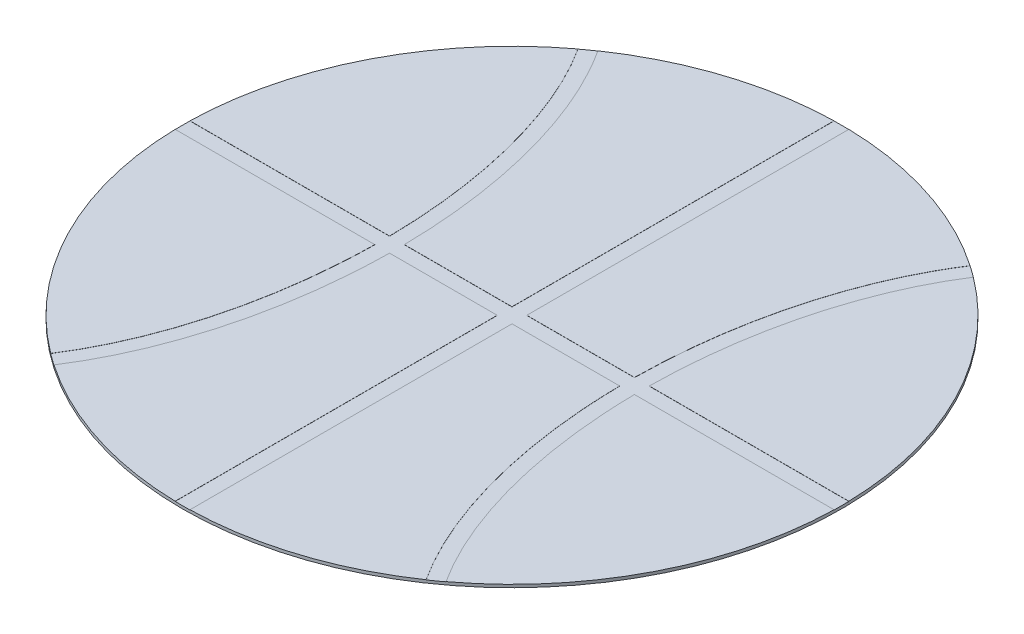
SolidWorks part; units mm, degrees
ref_plane "Front Plane" through (0, 0, 0) normal (0, 0, 1) x (1, 0, 0)
ref_plane "Top Plane" through (0, 0, 0) normal (0, 1, 0) x (1, 0, 0)
ref_plane "Right Plane" through (0, 0, 0) normal (1, 0, 0) x (0, 0, -1)
sketch "Sketch1" plane through (0, 0, 0) normal (0, 1, 0) x (1, 0, 0)
  circle A0 centre (0, 0) radius 22.3
  dimension "D1" = 44.6
extrude "Boss-Extrude1" add sketch "Sketch1" along normal blind 0.2
sketch "Sketch2" plane through (0, 0.2, 0) normal (0, 1, 0) x (1, 0, 0)
  line L0 (0, -0.11) -> (0, 0.11) construction
  line L1 (0.5, 24.8142) -> (-0.5, 24.8142)
  line L2 (0.5, 24.8142) -> (0.5, -24.8142)
  line L3 (0.5, -24.8142) -> (-0.5, -24.8142)
  line L4 (-0.5, 24.8142) -> (-0.5, -24.8142)
  line L5 (0.5, 24.8142) -> (-0.5, -24.8142) construction
  line L6 (0.5, -24.8142) -> (-0.5, 24.8142) construction
  line L7 (30.5234, -0.5) -> (-30.5234, -0.5)
  line L8 (30.5234, -0.5) -> (30.5234, 0.5)
  line L9 (30.5234, 0.5) -> (-30.5234, 0.5)
  line L10 (-30.5234, -0.5) -> (-30.5234, 0.5)
  line L11 (30.5234, -0.5) -> (-30.5234, 0.5) construction
  line L12 (30.5234, 0.5) -> (-30.5234, -0.5) construction
  circle A0 centre (0, 0) radius 22.3 construction
  ellipse E0 centre (-22.3, 0) end of major axis (-22.3, 24.7535) minor radius 14.5174
  ellipse E1 centre (-22.3, 0) end of major axis (-22.3, 23.7535) minor radius 13.5174
  ellipse E2 centre (22.3, 0) end of major axis (22.3, 24.7535) minor radius 14.5174
  ellipse E3 centre (22.3, 0) end of major axis (22.3, 23.7535) minor radius 13.5174
  point P0 (0, 0)
  point P5 (0, 0)
  circle M3 centre (0, 0) radius 22.3
  dimension "D1" = 1
  dimension "D2" = 1
  dimension "D3" = 1
  dimension "D4" = 1
extrude "Cut-Extrude1" cut sketch "Sketch2" against normal blind 0.01 contours E1 L9 E0 M3 | E1 E0 L7 M3 | E3 L7 E2 M3 | L9 E3 E2 M3 | E3 L7 L9 M3 | L7 E3 L9 E2 | L7 E2 L9 L2 | L2 L9 L4 L7 | L2 L7 L4 M3 | L9 L2 L4 M3 | E0 L7 L4 L9 | E1 L7 E0 L9 | L7 E1 L9 M3
